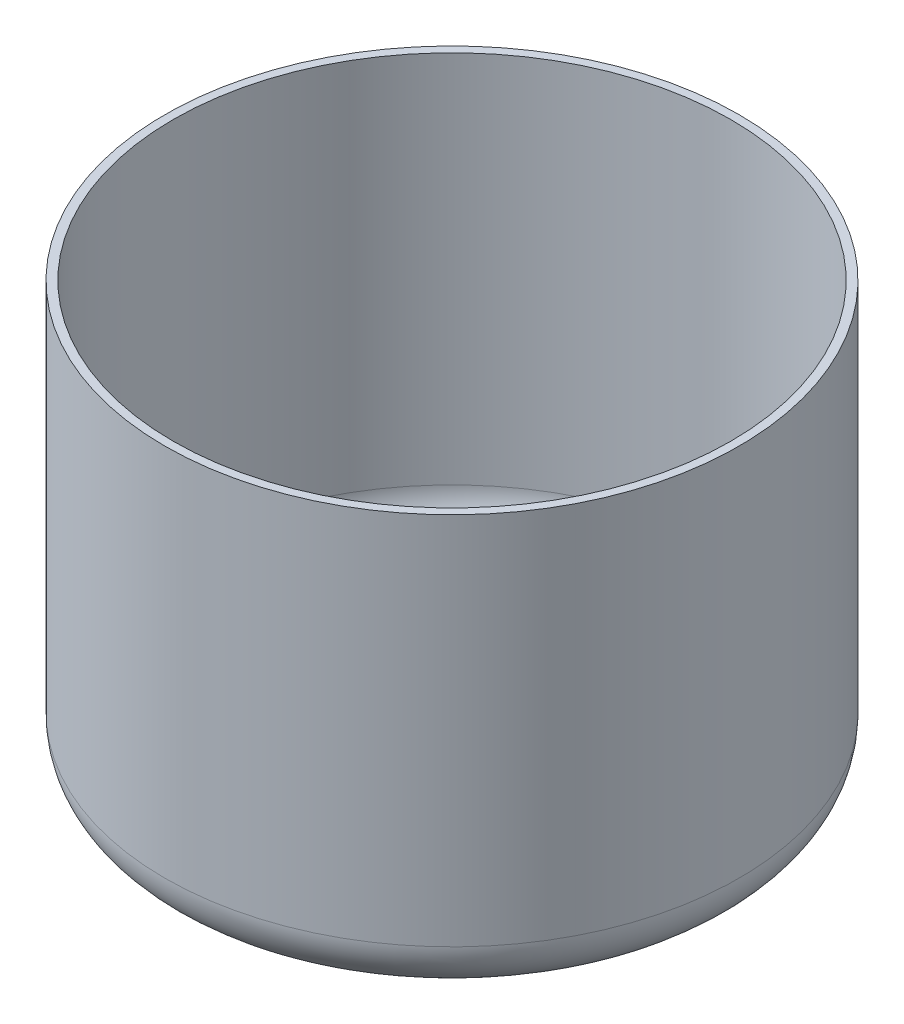
SolidWorks part; units mm, degrees
material "PVC Rigid"
ref_plane "Front Plane" through (0, 0, 0) normal (0, 0, 1) x (1, 0, 0)
ref_plane "Top Plane" through (0, 0, 0) normal (0, 1, 0) x (1, 0, 0)
ref_plane "Right Plane" through (0, 0, 0) normal (1, 0, 0) x (0, 0, -1)
sketch "Sketch1" plane through (0, 0, 0) normal (0, 1, 0) x (1, 0, 0)
  circle A0 centre (0, 0) radius 127
  dimension "D1" = 254
extrude "Boss-Extrude1" add sketch "Sketch1" along normal blind 190.5
fillet "Fillet1" radius 20 1 edges at (0, 0, 127)
shell "Shell1" thickness 3.81
